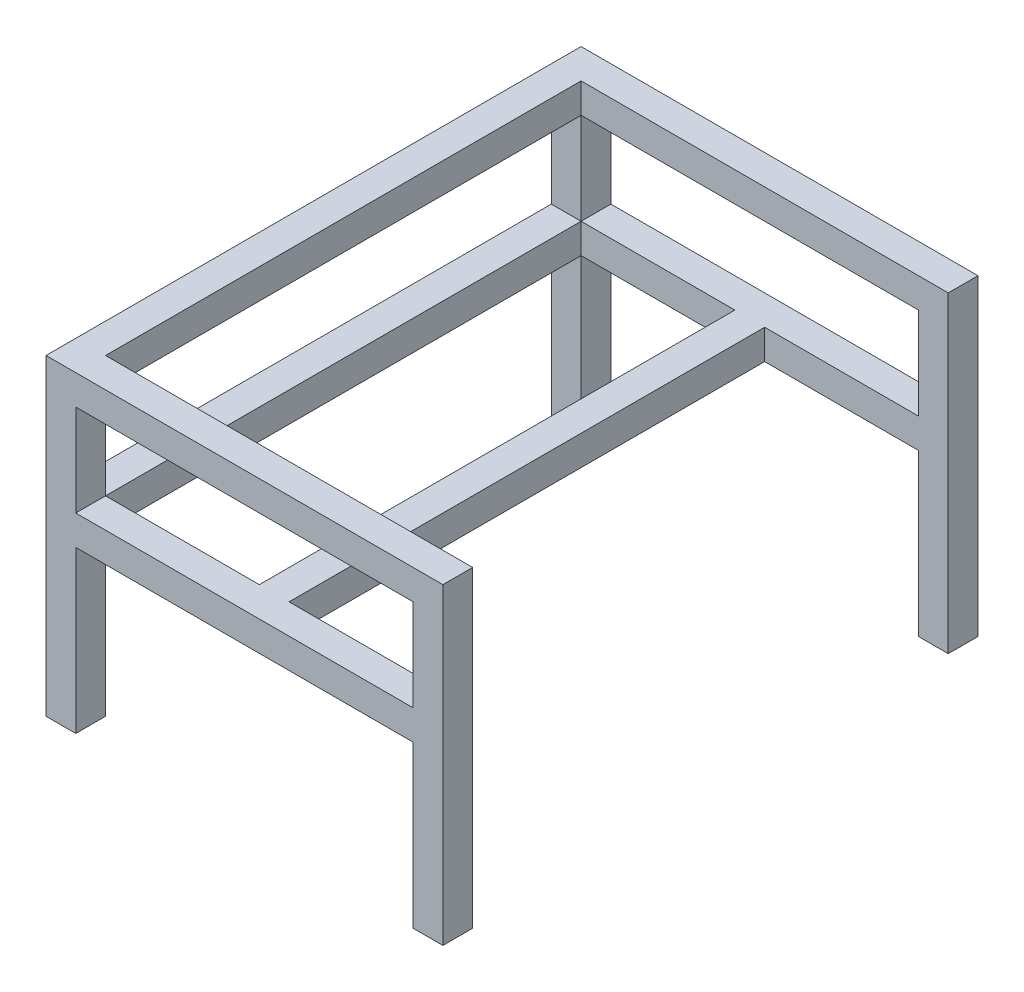
SolidWorks part; units mm, degrees
ref_plane "Alzado" through (0, 0, 0) normal (0, 0, 1) x (1, 0, 0)
ref_plane "Planta" through (0, 0, 0) normal (0, 1, 0) x (1, 0, 0)
ref_plane "Vista lateral" through (0, 0, 0) normal (1, 0, 0) x (0, 0, -1)
sketch "Croquis1" plane through (0, 0, 0) normal (0, 1, 0) x (1, 0, 0)
  line L1 (-508.1, -685) -> (508.1, -685)
  line L2 (-508.1, -685) -> (-508.1, 685)
  line L3 (-508.1, 685) -> (508.1, 685)
  line L4 (508.1, -685) -> (508.1, 685)
  line L5 (-508.1, -685) -> (508.1, 685) construction
  line L6 (-508.1, 685) -> (508.1, -685) construction
  point P0 (0, 0)
  dimension "D1" = 1016.2
  dimension "D2" = 1370
extrude "Saliente-Extruir1" add sketch "Croquis1" along normal blind 800
sketch "Croquis2" plane through (0, 0, 0) normal (0, -1, 0) x (1, 0, 0)
  line L0 (508.1, 685) -> (508.1, -685) construction
  line L1 (431.9, 608.8) -> (431.9, 685)
  line L2 (-431.9, 685) -> (431.9, 685)
  line L3 (508.1, -685) -> (-508.1, -685) construction
  line L4 (-508.1, 685) -> (508.1, 685) construction
  line L5 (-431.9, -608.8) -> (431.9, 608.8) construction
  line L6 (-431.9, 608.8) -> (431.9, -608.8) construction
  line L7 (-508.1, 685) -> (508.1, 685) construction
  line L8 (-431.9, 608.8) -> (-508.1, 608.8)
  line L9 (-508.1, -685) -> (-508.1, 685) construction
  line L10 (-508.1, 608.8) -> (-508.1, -608.8)
  line L11 (-508.1, -608.8) -> (-431.9, -608.8)
  line L12 (-431.9, -608.8) -> (-431.9, -685)
  line L13 (508.1, -685) -> (-508.1, -685) construction
  line L14 (-431.9, -685) -> (431.9, -685)
  line L15 (431.9, -685) -> (431.9, -608.8)
  line L16 (431.9, -608.8) -> (508.1, -608.8)
  line L17 (508.1, -608.8) -> (508.1, 608.8)
  line L18 (508.1, 608.8) -> (431.9, 608.8)
  line L19 (-508.1, -685) -> (-508.1, 685) construction
  line L20 (-431.9, 685) -> (-431.9, 608.8)
  point P0 (0, 0)
  dimension "D1" = 76.2
  dimension "D2" = 76.2
  dimension "D3" = 76.2
  dimension "D4" = 76.2
  dimension "D5" = 76.2
  dimension "D6" = 76.2
extrude "Cortar-Extruir1" cut sketch "Croquis2" against normal blind 723.8
sketch "Croquis3" plane through (0, 800, 0) normal (0, 1, 0) x (1, 0, 0)
  line L0 (508.1, 0) -> (-508.1, 0) construction
  line L1 (508.1, -685) -> (508.1, 685) construction
  line L2 (-508.1, 685) -> (-508.1, -685) construction
  line L3 (-508.1, -685) -> (508.1, -685) construction
  line L4 (-431.9, -608.8) -> (431.9, -608.8)
  line L5 (-431.9, -608.8) -> (-431.9, 608.8)
  line L6 (-431.9, 608.8) -> (431.9, 608.8)
  line L7 (431.9, -608.8) -> (431.9, 608.8)
  line L8 (-431.9, -608.8) -> (431.9, 608.8) construction
  line L9 (-431.9, 608.8) -> (431.9, -608.8) construction
  point P6 (0, 0)
  dimension "D1" = 76.2
  dimension "D2" = 76.2
extrude "Cortar-Extruir2" cut sketch "Croquis3" against normal blind 76.2
sketch "Croquis5" plane through (-508.1, 0, 0) normal (-1, 0, 0) x (0, 0, 1)
  line L0 (-608.8, 723.8) -> (-608.8, 0) construction
  line L1 (-608.8, 488.8) -> (608.8, 488.8)
  line L2 (-608.8, 488.8) -> (-608.8, 412.6)
  line L3 (-608.8, 412.6) -> (608.8, 412.6)
  line L4 (608.8, 488.8) -> (608.8, 412.6)
  line L5 (608.8, 723.8) -> (608.8, 0) construction
  line L6 (608.8, 723.8) -> (-608.8, 723.8) construction
  dimension "D1" = 235
  dimension "D2" = 76.2
extrude "Saliente-Extruir2" add sketch "Croquis5" against normal up to surface (76.2 mm away) up to face at (-431.9, 361.9, -646.9)
sketch "Croquis6" plane through (0, 0, -685) normal (0, 0, -1) x (-1, 0, 0)
  line L0 (-431.9, 723.8) -> (-431.9, 0) construction
  line L1 (431.9, 488.8) -> (-431.9, 488.8)
  line L2 (431.9, 488.8) -> (431.9, 412.6)
  line L3 (431.9, 412.6) -> (-431.9, 412.6)
  line L4 (-431.9, 488.8) -> (-431.9, 412.6)
extrude "Saliente-Extruir3" add sketch "Croquis6" against normal up to surface (76.2 mm away) up to face at (470, 361.9, -608.8)
sketch "Croquis7" plane through (508.1, 0, 0) normal (1, 0, 0) x (0, 0, -1)
  line L1 (608.8, 488.8) -> (-608.8, 488.8)
  line L2 (608.8, 488.8) -> (608.8, 412.6)
  line L3 (608.8, 412.6) -> (-608.8, 412.6)
  line L4 (-608.8, 488.8) -> (-608.8, 412.6)
extrude "Saliente-Extruir4" add sketch "Croquis7" against normal up to surface (76.2 mm away) up to face at (431.9, 361.9, 646.9)
sketch "Croquis8" plane through (0, 0, 685) normal (0, 0, 1) x (1, 0, 0)
  line L1 (431.9, 488.8) -> (-431.9, 488.8)
  line L2 (431.9, 488.8) -> (431.9, 412.6)
  line L3 (431.9, 412.6) -> (-431.9, 412.6)
  line L4 (-431.9, 488.8) -> (-431.9, 412.6)
extrude "Saliente-Extruir5" add sketch "Croquis8" against normal up to surface (76.2 mm away) up to face at (-470, 606.3, 608.8)
sketch "Croquis9" plane through (0, 800, 0) normal (0, 1, 0) x (1, 0, 0)
  line L1 (431.9, 608.8) -> (508.1, 608.8)
  line L2 (431.9, 608.8) -> (431.9, -608.8)
  line L3 (431.9, -608.8) -> (508.1, -608.8)
  line L4 (508.1, 608.8) -> (508.1, -608.8)
extrude "Cortar-Extruir4" cut sketch "Croquis9" against normal up to surface (387.4 mm away) up to face at (470, 412.6, 0)
sketch "Croquis10" plane through (0, 0, -608.8) normal (0, 0, 1) x (1, 0, 0)
  line L0 (0, 488.8) -> (0, 412.6) construction
  line L1 (-431.9, 488.8) -> (431.9, 488.8) construction
  line L2 (431.9, 412.6) -> (-431.9, 412.6) construction
  line L4 (38.1, 412.6) -> (-38.1, 412.6)
  line L5 (38.1, 412.6) -> (38.1, 488.8)
  line L6 (38.1, 488.8) -> (-38.1, 488.8)
  line L7 (-38.1, 412.6) -> (-38.1, 488.8)
  line L8 (38.1, 412.6) -> (-38.1, 488.8) construction
  line L9 (38.1, 488.8) -> (-38.1, 412.6) construction
  point P6 (0, 450.7)
  dimension "D1" = 76.2
extrude "Saliente-Extruir6" add sketch "Croquis10" along normal up to surface (1217.6 mm away) up to face at (-470, 606.3, 608.8)
